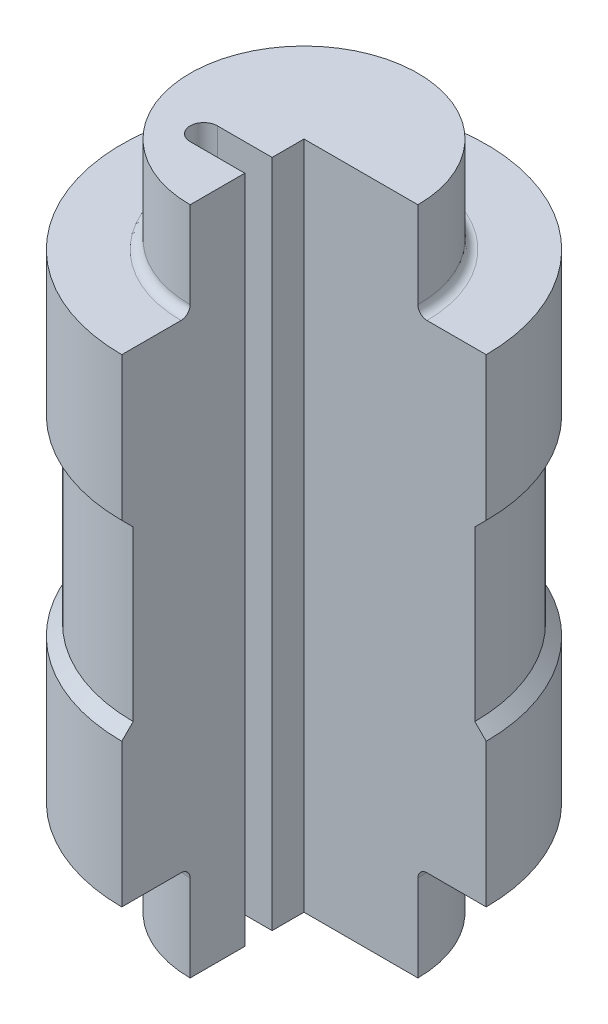
SolidWorks part; units mm, degrees
material "AISI 1020"
ref_plane "Front Plane" through (0, 0, 0) normal (0, 0, 1) x (1, 0, 0)
ref_plane "Top Plane" through (0, 0, 0) normal (0, 1, 0) x (1, 0, 0)
ref_plane "Right Plane" through (0, 0, 0) normal (1, 0, 0) x (0, 0, -1)
sketch "Sketch1" plane through (0, 0, 0) normal (0, 1, 0) x (1, 0, 0)
  circle A1 centre (0, 0) radius 40
  dimension "D2" = 80
extrude "Boss-Extrude1" add sketch "Sketch1" along normal blind 105
sketch "Sketch2" plane through (0, 105, 0) normal (0, 1, 0) x (1, 0, 0)
  circle A0 centre (0, 0) radius 25
  dimension "D1" = 50
extrude "Boss-Extrude2" add sketch "Sketch2" along normal blind 21
sketch "Sketch3" plane through (0, 0, 0) normal (0, -1, 0) x (-1, 0, 0)
  circle A0 centre (0, 0) radius 25
  dimension "D1" = 50
extrude "Boss-Extrude3" add sketch "Sketch3" along normal blind 21
fillet "Fillet1" radius 2 2 edges at (0, 0, -25) (0, 105, 25)
sketch "Sketch4" plane through (0, 0, 0) normal (1, 0, 0) x (0, 0, -1)
  line L0 (40, 73.5) -> (37.5, 71)
  line L2 (40, 0) -> (40, 105) construction
  line L3 (37.5, 71) -> (37.5, 34)
  line L4 (37.5, 34) -> (40, 31.5)
  line L5 (40, 73.5) -> (40, 31.5)
  dimension "D1" = 31.5
  dimension "D2" = 45
  dimension "D3" = 2.5
  dimension "D4" = 45
  dimension "D5" = 31.5
revolve "Cut-Revolve1" cut sketch "Sketch4" angle 360 about axis through (0, 105, 0) along (0, -1, 0)
sketch "Sketch5" plane through (0, -21, 0) normal (0, -1, 0) x (-1, 0, 0)
  line L1 (0, 0) -> (-44.6253, 0)
  line L2 (0, 0) -> (0, -44.1849)
  line L3 (0, -44.1849) -> (-44.6253, -44.1849)
  line L4 (-44.6253, 0) -> (-44.6253, -44.1849)
extrude "Cut-Extrude1" cut sketch "Sketch5" against normal through all
sketch "Sketch7" plane through (0, -21, 0) normal (0, -1, 0) x (-1, 0, 0)
  line L0 (12, -10) -> (-12, -10) construction
  line L1 (12, -13) -> (-12, -13)
  line L2 (12, -7) -> (-12, -7)
  line L3 (0, 0) -> (-25, 0) construction
  line L4 (0, -25) -> (0, 0) construction
  arc A0 (12, -13) -> (12, -7) centre (12, -10) ccw
  arc A1 (-12, -7) -> (-12, -13) centre (-12, -10) ccw
  point P2 (0, -10)
  dimension "D1" = 3
  dimension "D2" = 7
  dimension "D3" = 0
  dimension "D4" = 12
extrude "Cut-Extrude2" cut sketch "Sketch7" against normal through all
equation "\"a\"= 147"
equation "\"b\"= 21"
equation "\"c\"= 31.5"
equation "\"D1@Boss-Extrude2\"=\"b\""
equation "\"D1@Boss-Extrude3\"=\"b\""
equation "\"D1@Sketch4\"=\"c\""
equation "\"D5@Sketch4\"=\"c\""
equation "\"D1@Boss-Extrude1\"=\"a\"-2*\"b\""
